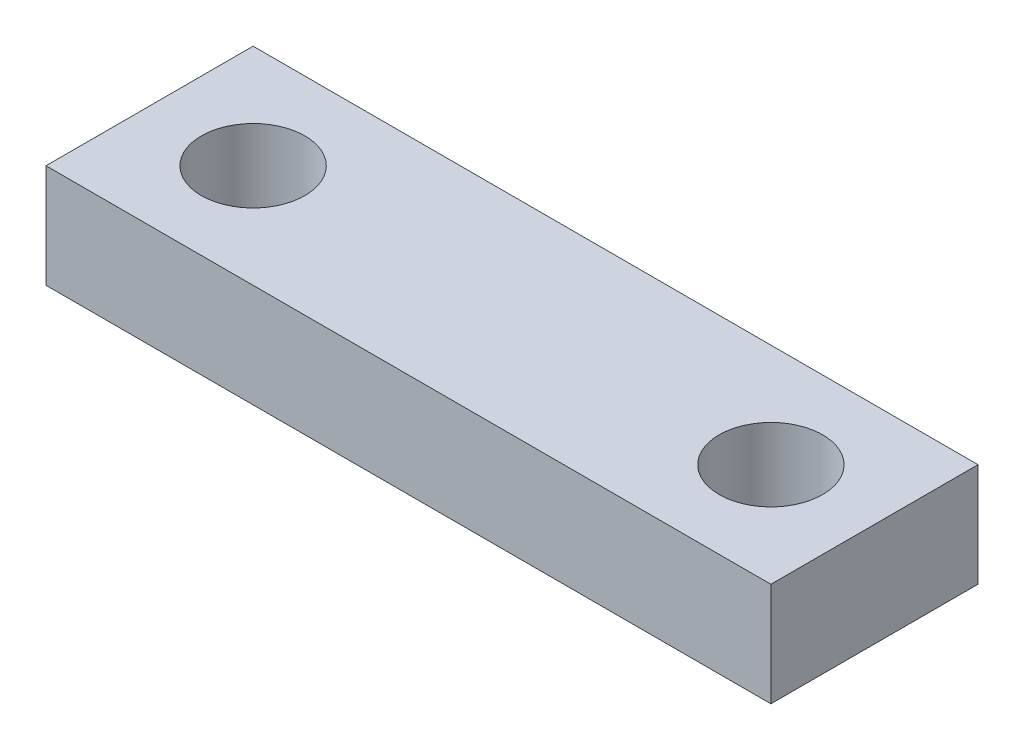
SolidWorks part; units mm, degrees
ref_plane "Front Plane" through (0, 0, 0) normal (0, 0, 1) x (1, 0, 0)
ref_plane "Top Plane" through (0, 0, 0) normal (0, 1, 0) x (1, 0, 0)
ref_plane "Right Plane" through (0, 0, 0) normal (1, 0, 0) x (0, 0, -1)
sketch "Sketch1" plane through (0, 0, 0) normal (0, 1, 0) x (1, 0, 0)
  line L0 (0, 0) -> (17.78, 0)
  line L1 (17.78, 0) -> (17.78, 5.08)
  line L2 (17.78, 5.08) -> (0, 5.08)
  line L3 (0, 5.08) -> (0, 0)
  circle A0 centre (2.54, 2.54) radius 1.27
  circle A1 centre (15.24, 2.54) radius 1.27
  point P10 (0, 2.54)
  point P11 (17.78, 2.54)
  dimension "D3" = 2.54
  dimension "D4" = 2.54
  dimension "D1" = 5.08
  dimension "D2" = 17.78
  dimension "D5" = 12.7
  dimension "D6" = 2.54
extrude "Boss-Extrude1" add sketch "Sketch1" along normal blind 2.54
